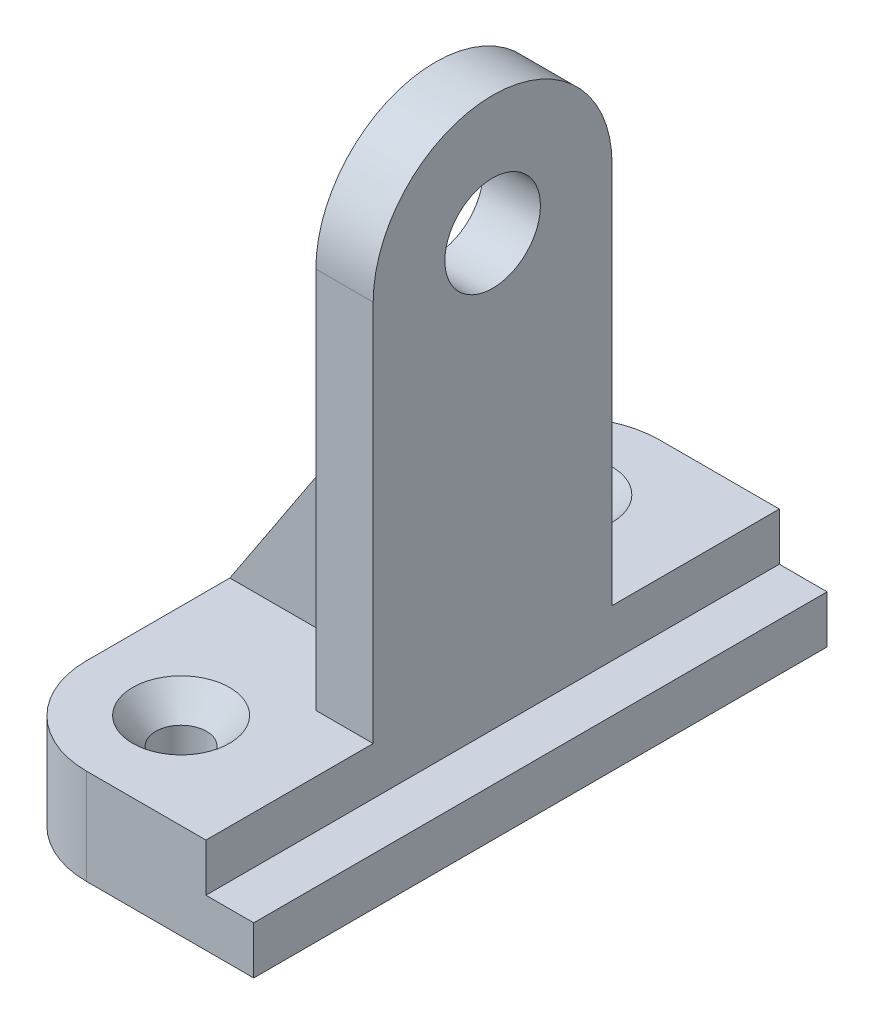
SolidWorks part; units mm, degrees
ref_plane "Front Plane" through (0, 0, 0) normal (0, 0, 1) x (1, 0, 0)
ref_plane "Top Plane" through (0, 0, 0) normal (0, 1, 0) x (1, 0, 0)
ref_plane "Right Plane" through (0, 0, 0) normal (1, 0, 0) x (0, 0, -1)
sketch "Sketch1" plane through (0, 0, 0) normal (0, 0, 1) x (1, 0, 0)
  line L0 (0, 0) -> (-34.925, 0)
  line L1 (-34.925, 0) -> (-34.925, 12.7)
  line L2 (-34.925, 12.7) -> (-6.35, 12.7)
  line L3 (-6.35, 12.7) -> (-6.35, 6.35)
  line L4 (-6.35, 6.35) -> (0, 6.35)
  line L5 (0, 6.35) -> (0, 0)
  dimension "D1" = 34.925
  dimension "D2" = 12.7
  dimension "D3" = 6.35
  dimension "D4" = 6.35
extrude "Boss-Extrude1" add sketch "Sketch1" along normal mid plane 76.2
sketch "Sketch2" plane through (-6.35, 0, 0) normal (1, 0, 0) x (0, 0, -1)
  line L0 (-15.875, 63.5) -> (-15.875, 12.7)
  line L1 (-38.1, 12.7) -> (38.1, 12.7) construction
  line L2 (15.875, 63.5) -> (15.875, 12.7)
  line L3 (-15.875, 12.7) -> (15.875, 12.7)
  line L4 (-38.1, 0) -> (38.1, 0) construction
  circle A0 centre (0, 63.5) radius 15.875
  circle A1 centre (0, 63.5) radius 6.35
  line M2 (38.1, 12.7) -> (-38.1, 12.7)
  dimension "D1" = 31.75
  dimension "D2" = 12.7
  dimension "D3" = 63.5
extrude "Boss-Extrude2" add sketch "Sketch2" against normal blind 7.62 contours A0 L0 L2 M2 | A0 A1
sketch "Sketch7" plane through (0, 0, 0) normal (0, 0, 1) x (1, 0, 0)
  line L0 (-13.97, 63.5) -> (-13.97, 12.7) construction
  line L1 (-6.35, 12.7) -> (-34.925, 12.7) construction
  line L2 (-13.97, 44.45) -> (-13.97, 12.7)
  line L3 (-13.97, 12.7) -> (-34.925, 12.7)
  line L4 (-34.925, 12.7) -> (-13.97, 44.45)
  dimension "D1" = 31.75
extrude "Boss-Extrude3" add sketch "Sketch7" along normal mid plane 12.7
fillet "Fillet1" radius 12.7 2 edges at (-34.925, 6.35, -38.1) (-34.925, 6.35, 38.1)
hole_wizard "CSK for 1/4 Flat Head Machine Screw1" positions "Sketch8" profile "Sketch9" countersink size "1/4" standard "ANSI Inch" end condition through all
sketch "Sketch8" plane through (0, 12.7, 0) normal (0, 1, 0) x (1, 0, 0)
  line L0 (0, 0) -> (-34.925, 0) construction
  line L1 (-34.925, -6.35) -> (-34.925, 6.35) construction
  line L3 (0, -38.1) -> (0, 38.1) construction
  point P0 (-22.352, 25.4)
  point P2 (-22.352, -25.4)
  point P12 (0, 0)
  point P13 (0, 0)
  dimension "D1" = 50.8
  dimension "D2" = 22.352
sketch "Sketch9" plane through (-22.352, 12.7, -25.4) normal (1, 0, 0) x (0, 0, 1)
  line L0 (0, 0) -> (0, 12.7)
  line L1 (0, 12.7) -> (3.3782, 12.7)
  line L2 (3.3782, 12.7) -> (3.3782, 3.5209)
  line L3 (3.3782, 3.5209) -> (6.4389, 0)
  line L5 (6.4389, 0) -> (0, 0)
  line L6 (-3.3782, 3.5209) -> (-6.4389, 0) construction
  line L11 (0, -6.35) -> (0, 107.95) construction
  dimension "Thru Hole Dia." = 6.7564
  dimension "Thru Hole Depth" = 12.7
  dimension "Near C'Sink Dia." = 12.8778
  dimension "Near C'Sink Angle" = 82
ref_plane "Plane4" through (-34.925, 12.7, 38.1) normal (-1, 0, 0) x (0, 0, 1)
ref_plane "Plane1" through (-34.925, 12.7, 38.1) normal (-1, 0, 0) x (0, 0, 1)
ref_plane "Plane2" through (-34.925, 12.7, 38.1) normal (-1, 0, 0) x (0, 0, 1)
ref_plane "Plane3" through (-34.925, 12.7, 38.1) normal (-1, 0, 0) x (0, 0, 1)
